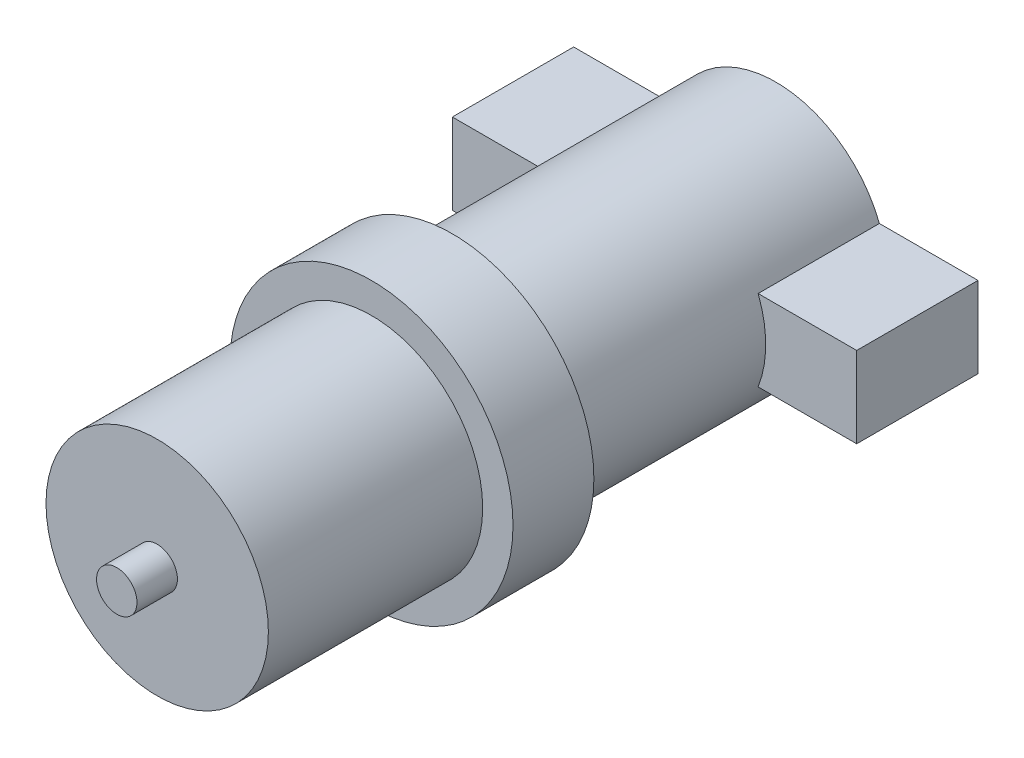
SolidWorks part; units mm, degrees
ref_plane "Front Plane" through (0, 0, 0) normal (0, 0, 1) x (1, 0, 0)
ref_plane "Top Plane" through (0, 0, 0) normal (0, 1, 0) x (1, 0, 0)
ref_plane "Right Plane" through (0, 0, 0) normal (1, 0, 0) x (0, 0, -1)
sketch "Sketch1" plane through (0, 0, 0) normal (0, 0, 1) x (1, 0, 0)
  circle A0 centre (0, 0) radius 27.5
  dimension "D1" = 55
extrude "Boss-Extrude1" add sketch "Sketch1" along normal blind 30
sketch "Sketch2" plane through (0, 0, 30) normal (0, 0, 1) x (1, 0, 0)
  circle A0 centre (0, 0) radius 35
  dimension "D1" = 70
extrude "Boss-Extrude2" add sketch "Sketch2" along normal blind 20
sketch "Sketch3" plane through (0, 0, 50) normal (0, 0, 1) x (1, 0, 0)
  circle A0 centre (0, 0) radius 27.5
  circle A1 centre (0, 0) radius 27.5 construction
extrude "Boss-Extrude3" add sketch "Sketch3" along normal blind 53
sketch "Sketch4" plane through (0, 0, 103) normal (0, 0, 1) x (1, 0, 0)
  circle A0 centre (0, 0) radius 5
  dimension "D1" = 10
extrude "Boss-Extrude4" add sketch "Sketch4" along normal blind 10
sketch "Sketch5" plane through (0, 0, 0) normal (0, 0, -1) x (-1, 0, 0)
  circle A0 centre (0, 0) radius 27.5
  circle A1 centre (0, 0) radius 27.5 construction
extrude "Boss-Extrude5" add sketch "Sketch5" along normal blind 50
sketch "Sketch8" plane through (0, 0, -50) normal (0, 0, -1) x (-1, 0, 0)
  line L1 (-50, -10) -> (50, -10)
  line L2 (-50, -10) -> (-50, 10)
  line L3 (-50, 10) -> (50, 10)
  line L4 (50, -10) -> (50, 10)
  line L5 (-50, -10) -> (50, 10) construction
  line L6 (-50, 10) -> (50, -10) construction
  point P0 (0, 0)
  dimension "D1" = 20
  dimension "D2" = 100
extrude "Boss-Extrude6" add sketch "Sketch8" against normal blind 30
